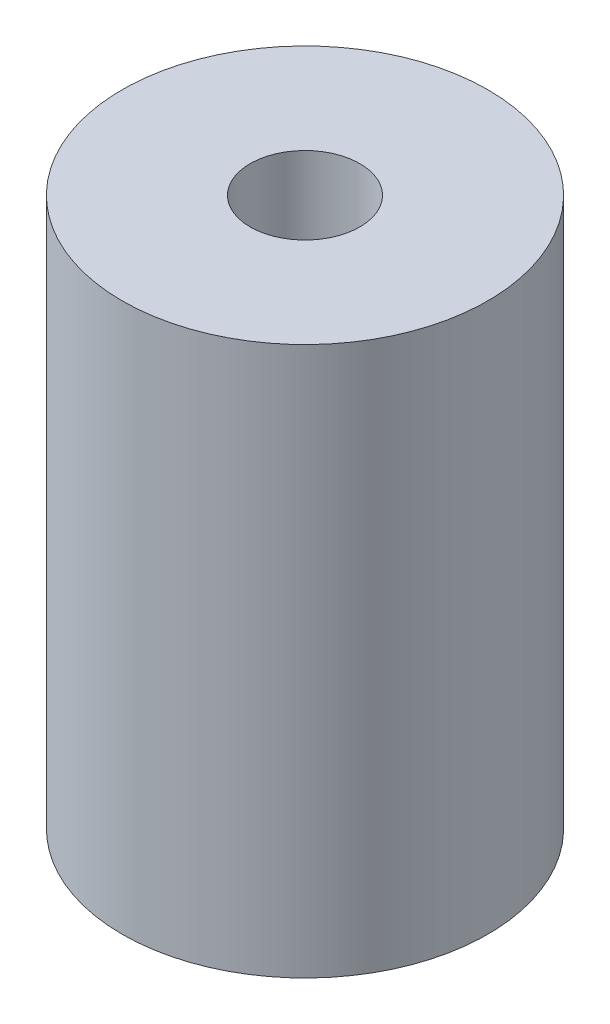
SolidWorks part; units mm, degrees
ref_plane "前视基准面" through (0, 0, 0) normal (0, 0, 1) x (1, 0, 0)
ref_plane "上视基准面" through (0, 0, 0) normal (0, 1, 0) x (1, 0, 0)
ref_plane "右视基准面" through (0, 0, 0) normal (1, 0, 0) x (0, 0, -1)
sketch "草图1" plane through (0, 0, 0) normal (0, 1, 0) x (1, 0, 0)
  circle A0 centre (0, 0) radius 3
  circle A1 centre (0, 0) radius 10
  dimension "D1" = 6
  dimension "D2" = 20
extrude "凸台-拉伸1" add sketch "草图1" along normal blind 30
